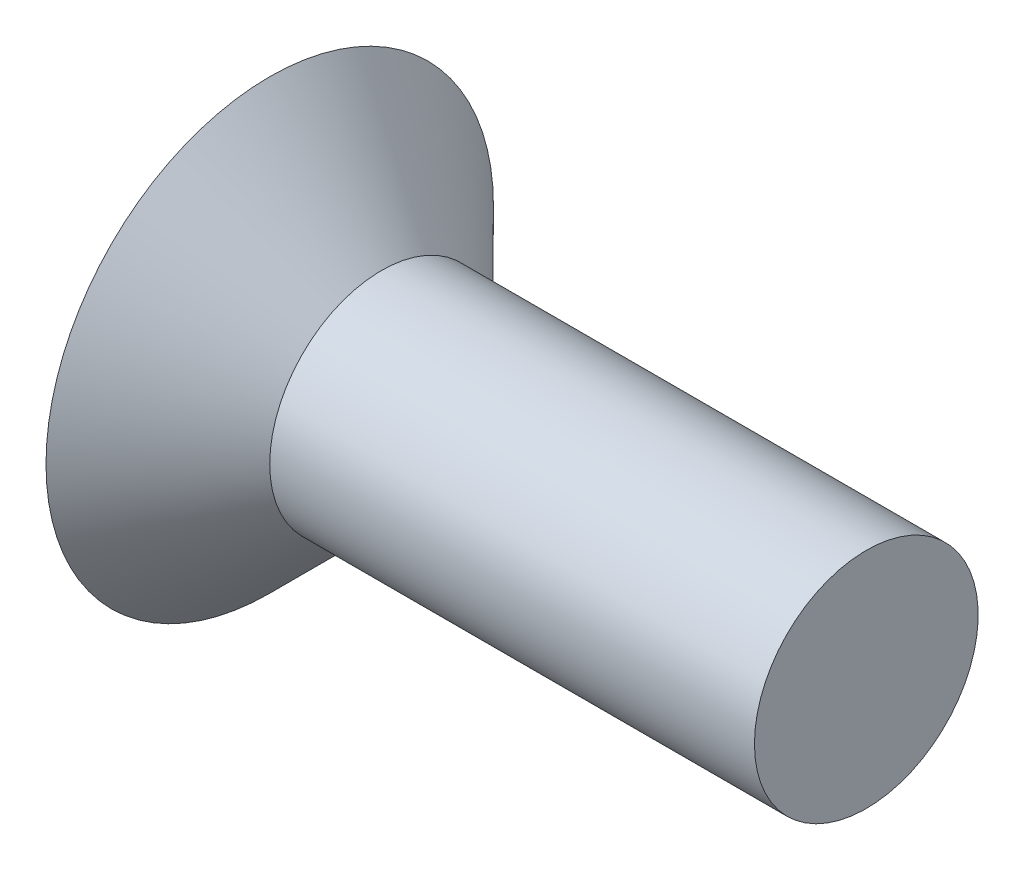
SolidWorks part; units mm, degrees
material "普通碳钢"
ref_plane "前视基准面" through (0, 0, 0) normal (0, 0, 1) x (1, 0, 0)
ref_plane "上视基准面" through (0, 0, 0) normal (0, 1, 0) x (1, 0, 0)
ref_plane "右视基准面" through (0, 0, 0) normal (1, 0, 0) x (0, 0, -1)
sketch "草图1" plane through (0, 0, 0) normal (0, 0, 1) x (1, 0, 0)
  line L0 (0, 0) -> (0, 3)
  line L5 (0, 0) -> (8, 0) construction
  line L6 (8, 0) -> (8, 1.5)
  line L7 (8, 1.5) -> (1.5, 1.5)
  line L8 (1.5, 1.5) -> (0, 3)
  dimension "D1" = 3
  dimension "D2" = 8
  dimension "D3" = 6
  dimension "D5" = 45
revolve "旋转1" add sketch "草图1" angle 360 about L5
cosmetic thread "装饰螺纹线2" parameters "D2"=1.221
sketch "草图2" plane through (0, 0, 0) normal (-1, 0, 0) x (0, 0, 1)
  line L1 (0, 1.1547) -> (-1, 0.5774)
  line L2 (-1, 0.5774) -> (-1, -0.5774)
  line L3 (-1, -0.5774) -> (0, -1.1547)
  line L4 (0, -1.1547) -> (1, -0.5774)
  line L5 (1, -0.5774) -> (1, 0.5774)
  line L6 (1, 0.5774) -> (0, 1.1547)
  circle A0 centre (0, 0) radius 1 construction
  dimension "D1" = 1
extrude "切除-拉伸1" cut sketch "草图2" against normal blind 1
